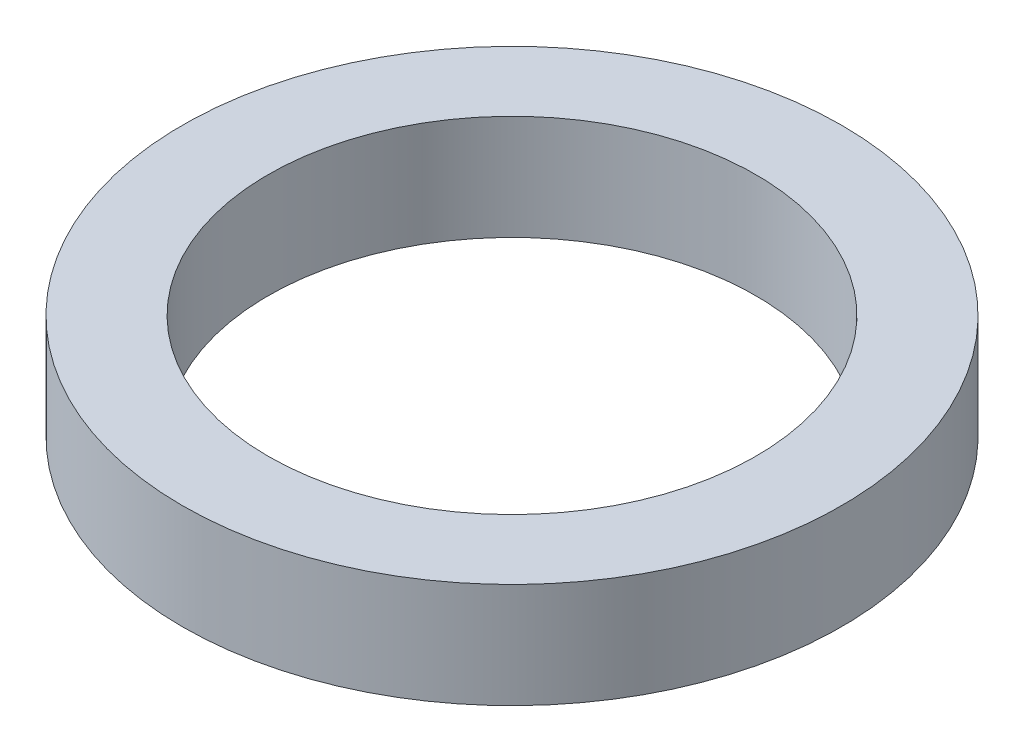
SolidWorks part; units mm, degrees
material "1023 Karbon Çeliği Levha (SS)"
ref_plane "Ön Düzlem" through (0, 0, 0) normal (0, 0, 1) x (1, 0, 0)
ref_plane "Üst Düzlem" through (0, 0, 0) normal (0, 1, 0) x (1, 0, 0)
ref_plane "Sağ Düzlem" through (0, 0, 0) normal (1, 0, 0) x (0, 0, -1)
sketch "Çizim1" plane through (0, 0, 0) normal (0, 1, 0) x (1, 0, 0)
  circle A0 centre (0, 0) radius 17.24
extrude "Yükseklik-Ekstrüzyon1" add sketch "Çizim1" along normal blind 5.49
sketch "Çizim2" plane through (0, 5.49, 0) normal (0, 1, 0) x (1, 0, 0)
  circle A0 centre (0, 0) radius 12.76
extrude "Kes-Ekstrüzyon1" cut sketch "Çizim2" against normal blind 8.49 and the other way blind 7
